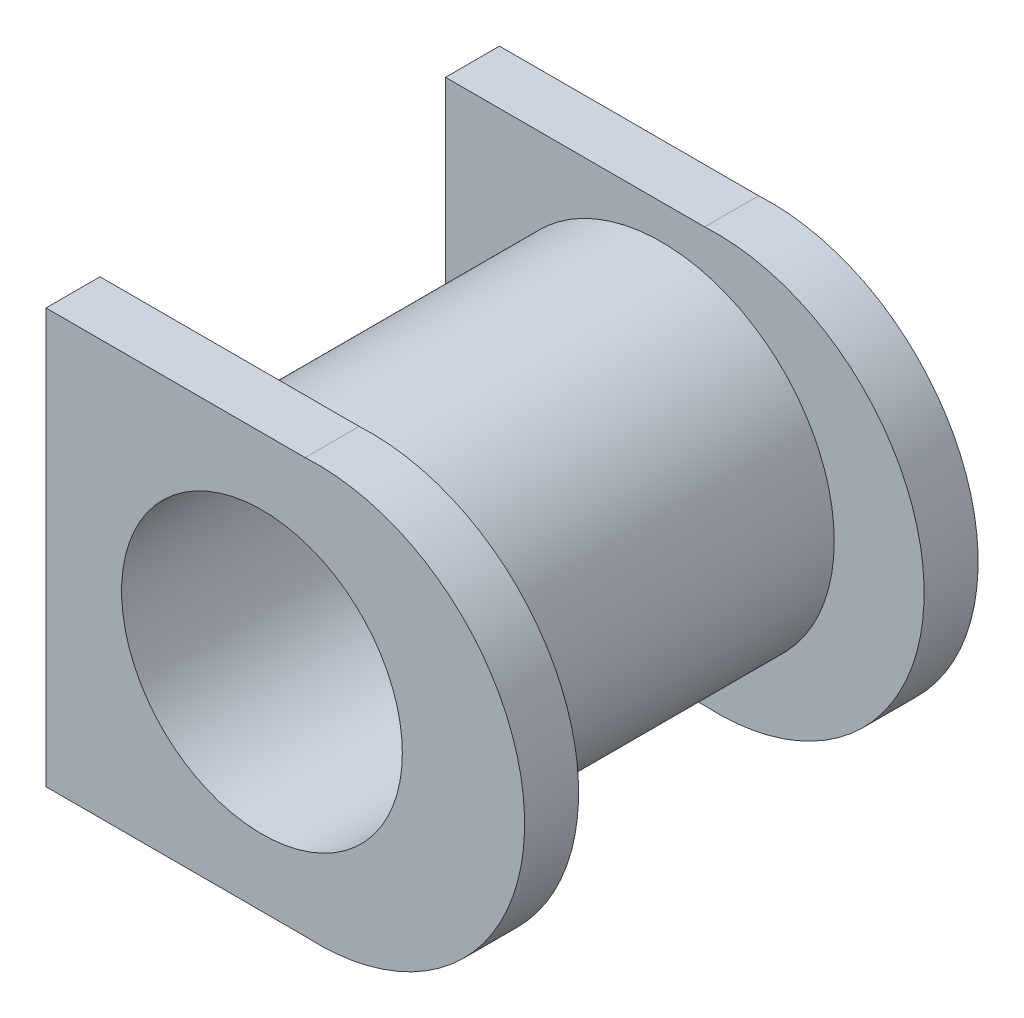
SolidWorks part; units mm, degrees
ref_plane "Front Plane" through (0, 0, 0) normal (0, 0, 1) x (1, 0, 0)
ref_plane "Top Plane" through (0, 0, 0) normal (0, 1, 0) x (1, 0, 0)
ref_plane "Right Plane" through (0, 0, 0) normal (1, 0, 0) x (0, 0, -1)
sketch "Sketch1" plane through (0, 0, 0) normal (0, 0, 1) x (1, 0, 0)
  line L1 (-30, -48) -> (30, -48)
  line L2 (-30, -48) -> (-30, 48)
  line L3 (-30, 48) -> (30, 48)
  arc A1 (30, -48) -> (30, 48) centre (32.7361, 0) ccw
  point P0 (0, 0)
extrude "Boss-Extrude1" add sketch "Sketch1" along normal blind 12.5
sketch "Sketch2" plane through (0, 0, 12.5) normal (0, 0, 1) x (1, 0, 0)
  line L0 (6.875, 0) -> (-6.875, 0) construction
  line L1 (-30, 48) -> (-30, -48) construction
  circle A0 centre (20, 0) radius 40
  dimension "D1" = 50
  dimension "D2" = 80
extrude "Boss-Extrude2" add sketch "Sketch2" along normal blind 80
sketch "Sketch3" plane through (0, 0, 92.5) normal (0, 0, 1) x (1, 0, 0)
  line L0 (-30, 48) -> (-30, -48)
  line L1 (-30, -48) -> (30, -48)
  line L2 (-30, 48) -> (30, 48)
  arc A0 (30, 48) -> (30, -48) centre (32.7361, 0) cw
extrude "Boss-Extrude3" add sketch "Sketch3" along normal blind 12.5
sketch "Sketch6" plane through (0, 0, 12.5) normal (0, 0, 1) x (1, 0, 0)
  circle A0 centre (20, 0) radius 32.5
extrude "Cut-Extrude2" cut sketch "Sketch6" against normal through all both and the other way through all
